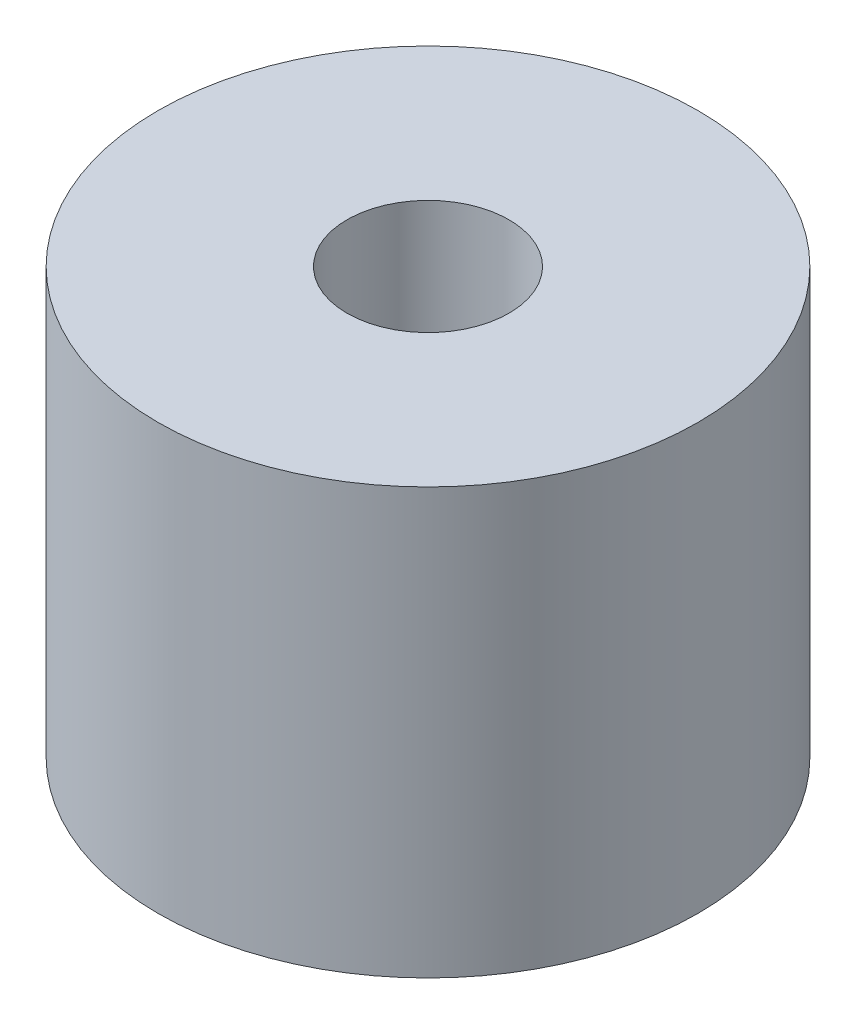
SolidWorks part; units mm, degrees
ref_plane "Front Plane" through (0, 0, 0) normal (0, 0, 1) x (1, 0, 0)
ref_plane "Top Plane" through (0, 0, 0) normal (0, 1, 0) x (1, 0, 0)
ref_plane "Right Plane" through (0, 0, 0) normal (1, 0, 0) x (0, 0, -1)
sketch "Sketch1" plane through (0, 0, 0) normal (0, 1, 0) x (1, 0, 0)
  circle A0 centre (0, 0) radius 12.7
  circle A1 centre (0, 0) radius 3.81
  dimension "D1" = 25.4
  dimension "D2" = 7.62
extrude "Boss-Extrude1" add sketch "Sketch1" along normal blind 20
